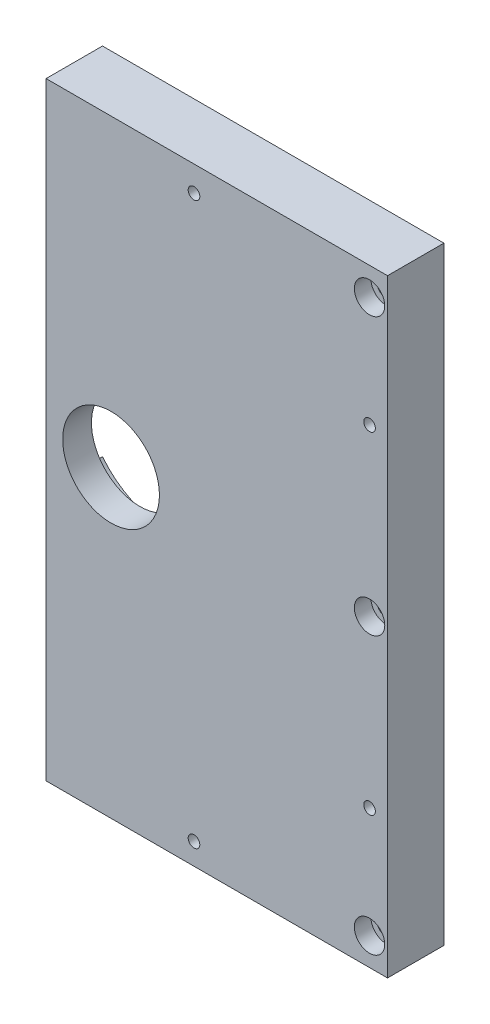
SolidWorks part; units mm, degrees
ref_plane "Plano frontal" through (0, 0, 0) normal (0, 0, 1) x (1, 0, 0)
ref_plane "Plano superior" through (0, 0, 0) normal (0, 1, 0) x (1, 0, 0)
ref_plane "Plano direito" through (0, 0, 0) normal (1, 0, 0) x (0, 0, -1)
sketch "Esboço1" plane through (0, 0, 0) normal (0, 0, 1) x (1, 0, 0)
  line L0 (-23.5, 110) -> (100, 110)
  line L1 (-23.5, -110) -> (100, -110)
  line L2 (-23.5, -110) -> (-23.5, -18.6481)
  line L5 (100, 110) -> (100, -110)
  line L6 (-23.5, -110) -> (-23.5, -18.6481) construction
  line L7 (-23.5, 18.6481) -> (-23.5, 110)
  arc A0 (-23.5, -18.6481) -> (-23.5, 18.6481) centre (0, 0) ccw construction
  arc A1 (-23.5, -18.6481) -> (-23.5, 18.6481) centre (0, 0) ccw
extrude "Ressalto-extrusão1" add sketch "Esboço1" along normal up to vertex (20.4 mm away)
hole_wizard "Rebaixo para SHCS M61" positions "Esboço11" profile "Esboço13" counterbore size "M6" standard "Ansi Metric" end condition through all
sketch "Esboço11" plane through (0, 0, 20.4) normal (0, 0, 1) x (1, 0, 0)
  point P3 (93.5, 100)
  point P6 (93.5, 0)
  point P15 (93.5, -100)
sketch "Esboço13" plane through (93.5, 100, 20.4) normal (1, 0, 0) x (0, -1, 0)
  line L0 (0, 0) -> (0, 20.4)
  line L1 (0, 20.4) -> (3.3, 20.4)
  line L3 (3.3, 20.4) -> (3.3, 6)
  line L4 (3.3, 6) -> (5.5, 6)
  line L5 (5.5, 6) -> (5.5, 0)
  line L7 (5.5, 0) -> (0, 0)
  line L11 (0, -6.35) -> (0, 107.95) construction
  dimension "Thru Hole Dia." = 6.6
  dimension "Thru Hole Depth" = 20.4
  dimension "C'Bore Dia." = 11
  dimension "C'Bore Depth" = 6
sketch "Esboço14" plane through (0, 0, 10) normal (0, 0, 1) x (1, 0, 0)
  line L0 (-23.5, -18.6481) -> (-23.5, 18.6481)
  circle A0 centre (0, 0) radius 17.5 construction
  circle A1 centre (0, 0) radius 17.5
  arc A2 (-23.5, -18.6481) -> (-23.5, 18.6481) centre (0, 0) ccw construction
  arc A3 (-23.5, -18.6481) -> (-23.5, 18.6481) centre (0, 0) ccw
extrude "Ressalto-extrusão2" add sketch "Esboço14" along normal up to vertex (10.4 mm away)
hole_wizard "Furo roscado de M5x0.81" positions "Esboço15" profile "Esboço16" tap size "M5x0.8" standard "Ansi Metric"
sketch "Esboço15" plane through (0, 0, 20.4) normal (0, 0, 1) x (1, 0, 0)
  point P0 (30, 100.8276)
  point P3 (93.5, 60)
  point P6 (93.5, -60)
  point P9 (30, -102.1949)
sketch "Esboço16" plane through (30, 100.8276, 20.4) normal (1, 0, 0) x (0, -1, 0)
  line L0 (0, 0) -> (0, 15.2618)
  line L1 (0, 15.2618) -> (2.1, 14)
  line L2 (2.1, 14) -> (2.1, 0)
  line L5 (2.1, 0) -> (0, 0)
  line L10 (0, 15.2618) -> (-2.1, 14) construction
  line L11 (0, -6.35) -> (0, 107.95) construction
  dimension "Tap Drill Dia." = 4.2
  dimension "Tap Drill Depth" = 14
  dimension "Drill Angle" = 118
cosmetic thread "Rosca de furo1" parameters "D1"=10, "D2"=5
cosmetic thread "Rosca de furo2" parameters "D1"=10, "D2"=5
cosmetic thread "Rosca de furo3" parameters "D1"=10, "D2"=5
cosmetic thread "Rosca de furo4" parameters "D1"=10, "D2"=5
